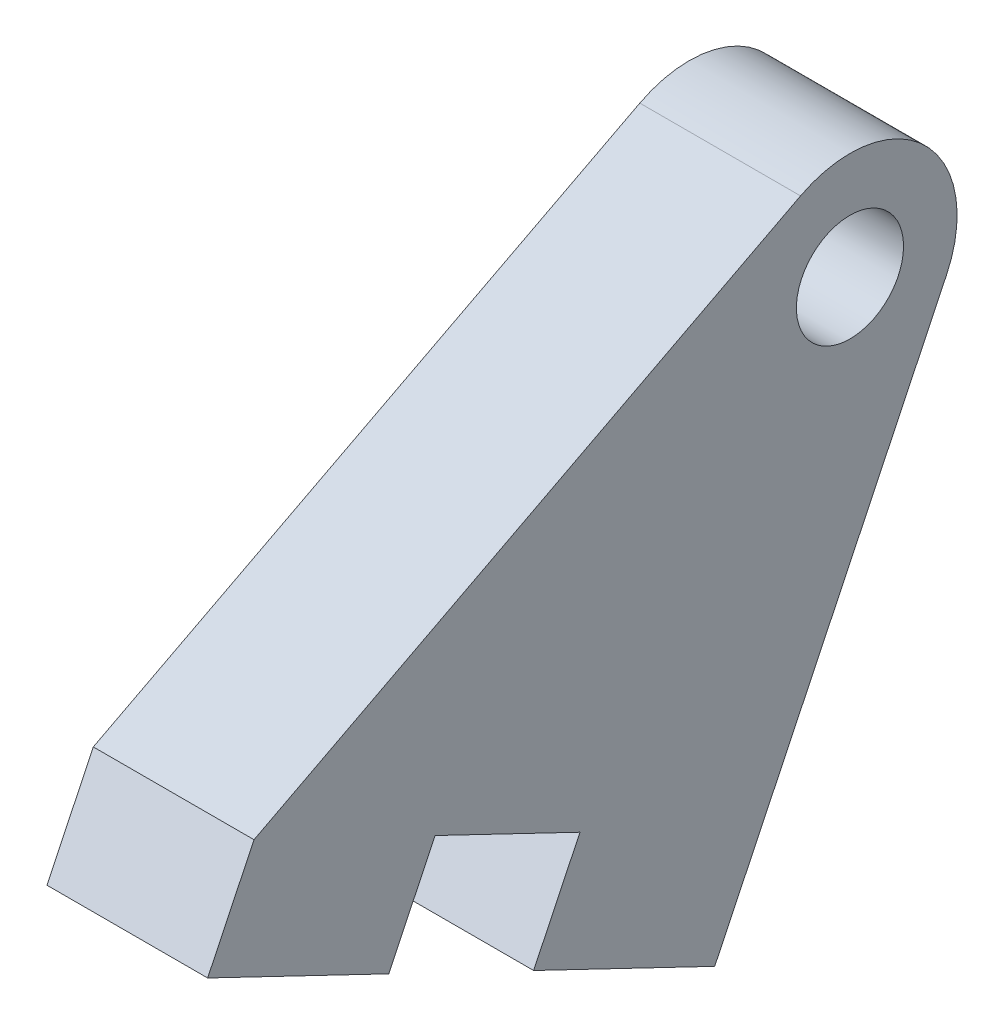
SolidWorks part; units mm, degrees
ref_plane "Front" through (0, 0, 0) normal (0, 0, 1) x (1, 0, 0)
ref_plane "Top" through (0, 0, 0) normal (0, 1, 0) x (1, 0, 0)
ref_plane "Right" through (0, 0, 0) normal (1, 0, 0) x (0, 0, -1)
sketch "Sketch1" plane through (0, 0, 0) normal (1, 0, 0) x (0, 0, -1)
  line L0 (-96.6269, 8.8786) -> (-101.7279, 6.225)
  line L1 (-101.7279, 6.225) -> (-102.1607, 5.3235)
  line L2 (-102.1607, 5.3235) -> (-97.4279, 3.0513)
  line L3 (-97.4279, 3.0513) -> (-95.2639, 7.5587)
  line L4 (-99.7943, 4.1874) -> (-97.8467, 8.2441) construction
  line L5 (-100.4704, 4.512) -> (-100.0376, 5.4135)
  line L6 (-100.0376, 5.4135) -> (-98.6854, 4.7643)
  line L7 (-98.6854, 4.7643) -> (-99.1182, 3.8628)
  circle A0 centre (-96.1653, 7.9915) radius 0.5
  circle A1 centre (-96.1653, 7.9915) radius 1
  point P12 (-99.3615, 5.0889)
  dimension "D2" = 1
  dimension "D3" = 0.5
  dimension "D1" = 1
  dimension "D4" = 5.25
  dimension "D5" = 5
  dimension "D6" = 1
  dimension "D7" = 1.5
extrude "Boss-Extrude1" add sketch "Sketch1" along normal blind 1.5 contours A1 L0 L1 L2 L3 | A1 A0 | L6 L4 L0 L1 L2 L5
